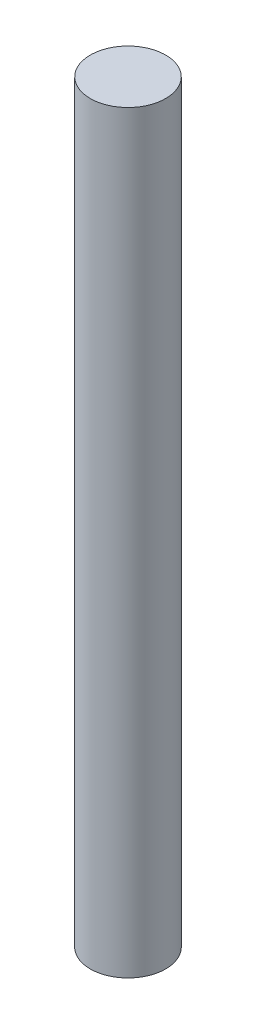
SolidWorks part; units mm, degrees
ref_plane "Front Plane" through (0, 0, 0) normal (0, 0, 1) x (1, 0, 0)
ref_plane "Top Plane" through (0, 0, 0) normal (0, 1, 0) x (1, 0, 0)
ref_plane "Right Plane" through (0, 0, 0) normal (1, 0, 0) x (0, 0, -1)
sketch "草图1" plane through (0, 0, 0) normal (0, 1, 0) x (1, 0, 0)
  circle A0 centre (0, 0) radius 5
extrude "凸台-拉伸1" add sketch "草图1" along normal blind 100 contours A0
